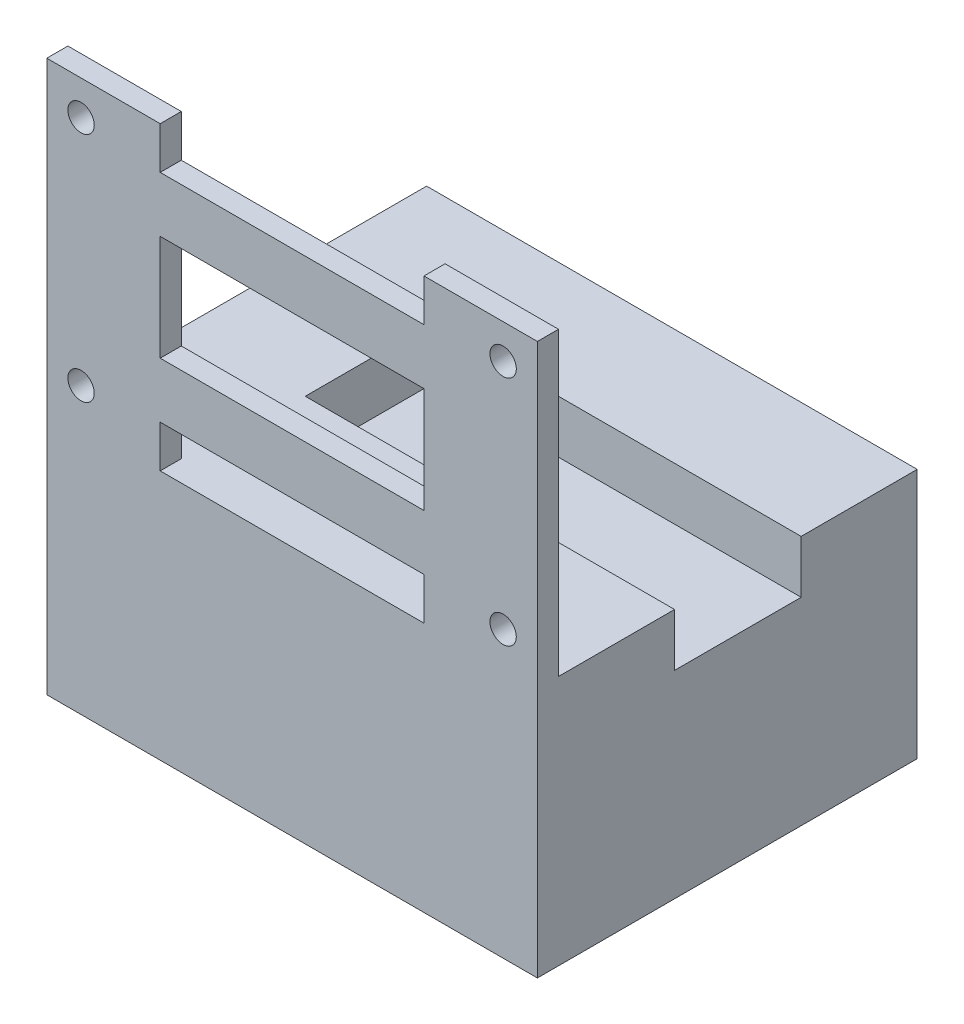
SolidWorks part; units mm, degrees
ref_plane "Front Plane" through (0, 0, 0) normal (0, 0, 1) x (1, 0, 0)
ref_plane "Top Plane" through (0, 0, 0) normal (0, 1, 0) x (1, 0, 0)
ref_plane "Right Plane" through (0, 0, 0) normal (1, 0, 0) x (0, 0, -1)
sketch "Sketch1" plane through (0, 0, 0) normal (0, 1, 0) x (1, 0, 0)
  line L1 (-23.25, -17) -> (23.25, -17)
  line L2 (-23.25, -17) -> (-23.25, 17)
  line L3 (-23.25, 17) -> (23.25, 17)
  line L4 (23.25, -17) -> (23.25, 17)
  line L5 (-23.25, -17) -> (23.25, 17) construction
  line L6 (-23.25, 17) -> (23.25, -17) construction
  point P0 (0, 0)
  dimension "D1" = 46.5
  dimension "D2" = 34
extrude "Boss-Extrude1" add sketch "Sketch1" along normal blind 13.75
sketch "Sketch2" plane through (0, 0, 17) normal (0, 0, 1) x (1, 0, 0)
  line L1 (-23.25, 0) -> (23.25, 0)
  line L2 (-23.25, 0) -> (-23.25, 42.25)
  line L3 (-23.25, 42.25) -> (23.25, 42.25)
  line L4 (23.25, 0) -> (23.25, 42.25)
  dimension "D1" = 46.5
  dimension "D2" = 42.25
extrude "Boss-Extrude2" add sketch "Sketch2" along normal blind 2
sketch "Sketch3" plane through (0, 0, 19) normal (0, 0, 1) x (1, 0, 0)
  line L0 (-23.25, 28) -> (23.25, 28) construction
  line L1 (-12.5, 33) -> (12.5, 33)
  line L2 (-12.5, 33) -> (-12.5, 23)
  line L3 (-12.5, 23) -> (12.5, 23)
  line L4 (12.5, 33) -> (12.5, 23)
  line L5 (23.25, 0) -> (23.25, 42.25) construction
  line L6 (23.25, 42.25) -> (-23.25, 42.25) construction
  line L7 (-23.25, 42.25) -> (-23.25, 0) construction
  circle A0 centre (-20, 39) radius 1.25
  circle A2 centre (20, 39) radius 1.25
  circle A4 centre (20, 17) radius 1.25
  circle A5 centre (-20, 17) radius 1.25
  dimension "D1" = 2.5
  dimension "D11" = 2.5
  dimension "D2" = 10
  dimension "D3" = 25
  dimension "D4" = 5
  dimension "D5" = 10.75
  dimension "D6" = 14.25
  dimension "D7" = 3.25
  dimension "D8" = 3.25
  dimension "D9" = 3.25
  dimension "D10" = 3.25
extrude "Cut-Extrude1" cut sketch "Sketch3" against normal up to next
sketch "Sketch4" plane through (0, 13.75, 0) normal (0, 1, 0) x (1, 0, 0)
  line L0 (23.25, -17) -> (23.25, 17) construction
  line L1 (23.25, 6) -> (-11.75, 6)
  line L2 (23.25, 6) -> (23.25, -6)
  line L3 (23.25, -6) -> (-11.75, -6)
  line L4 (-11.75, 6) -> (-11.75, -6)
  line L5 (23.25, 17) -> (-23.25, 17) construction
  dimension "D1" = 35
  dimension "D2" = 12
  dimension "D3" = 11
extrude "Cut-Extrude2" cut sketch "Sketch4" against normal blind 5
sketch "Sketch6" plane through (0, 0, 0) normal (0, -1, 0) x (1, 0, 0)
  line L0 (16.25, -10) -> (16.25, 12)
  line L1 (23.25, -17) -> (-23.25, -17)
  line L2 (23.25, -17) -> (23.25, 19)
  line L3 (23.25, 19) -> (-23.25, 19)
  line L4 (-23.25, -17) -> (-23.25, 19)
  line L5 (16.25, 12) -> (-16.25, 12)
  line L6 (-16.25, -10) -> (-16.25, 12)
  line L7 (16.25, -10) -> (-16.25, -10)
  circle A0 centre (16.25, -10) radius 2
  circle A1 centre (16.25, 12) radius 2
  circle A2 centre (-16.25, -10) radius 2
  circle A3 centre (-16.25, 12) radius 2
  line M9 (23.25, -17) -> (23.25, 19)
  line M10 (23.25, 19) -> (-23.25, 19)
  line M11 (-23.25, 19) -> (-23.25, -17)
  line M12 (-23.25, -17) -> (23.25, -17)
  dimension "D2" = 4
  dimension "D3" = 4
  dimension "D4" = 4
  dimension "D5" = 4
  dimension "D1" = 7
extrude "Boss-Extrude3" add sketch "Sketch6" along normal blind 10 contours A3 L6 A2 L7 A0 L0 A1 L5 | A3 L5 A1 L0 A0 L7 A2 L6 M12 M9 M10 M11
sketch "Sketch7" plane through (0, 0, 17) normal (0, 0, -1) x (-1, 0, 0)
  line L0 (23.25, 13.75) -> (-23.25, 13.75) construction
  line L1 (-12.5, 13.75) -> (12.5, 13.75)
  line L2 (-12.5, 13.75) -> (-12.5, 17.75)
  line L3 (-12.5, 17.75) -> (12.5, 17.75)
  line L4 (12.5, 13.75) -> (12.5, 17.75)
  line L5 (-23.25, 42.25) -> (23.25, 42.25) construction
  line L6 (-12.5, 42.25) -> (12.5, 42.25)
  line L7 (-12.5, 42.25) -> (-12.5, 38.25)
  line L8 (-12.5, 38.25) -> (12.5, 38.25)
  line L9 (12.5, 42.25) -> (12.5, 38.25)
  dimension "D1" = 4
  dimension "D2" = 4
extrude "Cut-Extrude3" cut sketch "Sketch7" against normal blind 10
